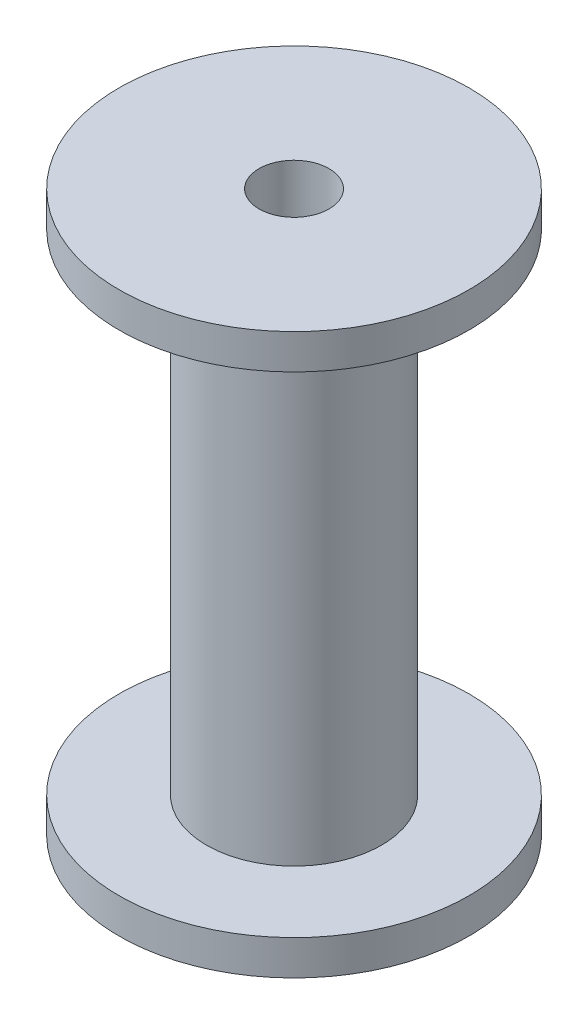
SolidWorks part; units mm, degrees
ref_plane "Front Plane" through (0, 0, 0) normal (0, 0, 1) x (1, 0, 0)
ref_plane "Top Plane" through (0, 0, 0) normal (0, 1, 0) x (1, 0, 0)
ref_plane "Right Plane" through (0, 0, 0) normal (1, 0, 0) x (0, 0, -1)
sketch "Sketch2" plane through (0, 0, 0) normal (0, 0, 1) x (1, 0, 0)
  line L0 (0, 0) -> (0, 203.2)
  line L1 (0, -55) -> (0, 55) construction
  line L2 (0, 203.2) -> (63.5, 203.2)
  line L3 (63.5, 203.2) -> (63.5, 190.5)
  line L4 (63.5, 190.5) -> (31.75, 190.5)
  line L5 (31.75, 190.5) -> (31.75, 12.7)
  line L6 (31.75, 12.7) -> (63.5, 12.7)
  line L7 (63.5, 12.7) -> (63.5, 0)
  line L8 (55, 0) -> (-55, 0) construction
  line L9 (63.5, 0) -> (0, 0)
  dimension "D1" = 63.5
  dimension "D2" = 31.75
  dimension "D3" = 177.8
  dimension "D4" = 12.7
  dimension "D5" = 12.7
revolve "Revolve1" add sketch "Sketch2" angle 360 about L0
sketch "Sketch3" plane through (0, 203.2, 0) normal (0, 1, 0) x (1, 0, 0)
  circle A0 centre (0, 0) radius 12.7
  dimension "D1" = 25.4
extrude "Cut-Extrude1" cut sketch "Sketch3" against normal through all
